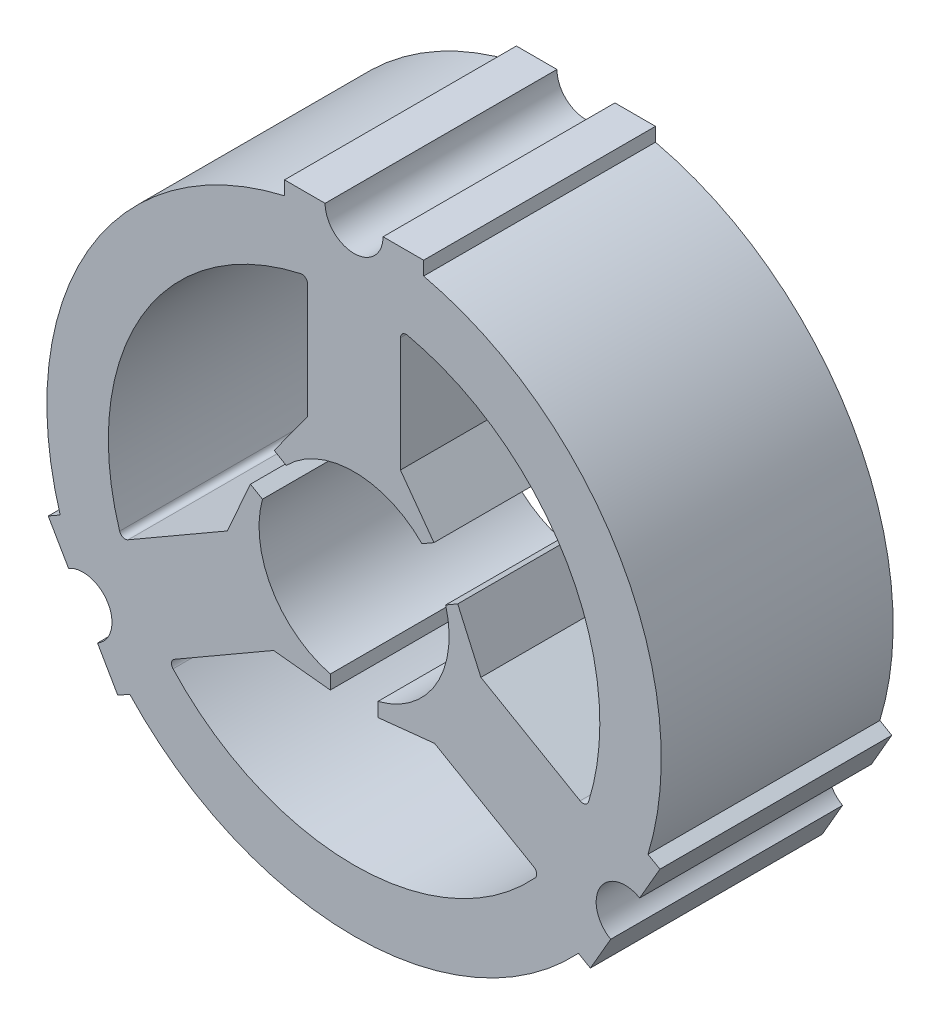
SolidWorks part; units mm, degrees
ref_plane "前视基准面" through (0, 0, 0) normal (0, 0, 1) x (1, 0, 0)
ref_plane "上视基准面" through (0, 0, 0) normal (0, 1, 0) x (1, 0, 0)
ref_plane "右视基准面" through (0, 0, 0) normal (1, 0, 0) x (0, 0, -1)
sketch "草图1" plane through (0, 0, 0) normal (0, 0, 1) x (1, 0, 0)
  line L0 (-21.4536, 0) -> (25.5305, 0) construction
  line L1 (0, 19.7631) -> (0, -19.5145) construction
  line L2 (-3, 13.5) -> (-3, 12.9059)
  line L3 (-1.25, 13.5) -> (-3, 13.5)
  line L4 (1.25, 13.5) -> (3, 13.5)
  line L5 (3, 13.5) -> (3, 12.9059)
  line L6 (13.1913, -4.1519) -> (12.6768, -3.8549)
  line L7 (12.3163, -5.6675) -> (13.1913, -4.1519)
  line L8 (11.0663, -7.8325) -> (10.1913, -9.3481)
  line L9 (10.1913, -9.3481) -> (9.6768, -9.051)
  line L10 (-10.1913, -9.3481) -> (-9.6768, -9.051)
  line L11 (-11.0663, -7.8325) -> (-10.1913, -9.3481)
  line L12 (-12.3163, -5.6675) -> (-13.1913, -4.1519)
  line L13 (-13.1913, -4.1519) -> (-12.6768, -3.8549)
  arc A0 (-3, 12.9059) -> (-12.6768, -3.8549) centre (0, 0) ccw
  circle A1 centre (0, 0) radius 4.1
  arc A2 (-1.25, 13.5) -> (1.25, 13.5) centre (0, 13.5) ccw
  arc A3 (12.3163, -5.6675) -> (11.0663, -7.8325) centre (11.6913, -6.75) ccw
  arc A4 (-11.0663, -7.8325) -> (-12.3163, -5.6675) centre (-11.6913, -6.75) ccw
  arc A5 (12.6768, -3.8549) -> (3, 12.9059) centre (0, 0) ccw
  arc A6 (-9.6768, -9.051) -> (9.6768, -9.051) centre (0, 0) ccw
  circle A7 centre (0, 0) radius 13.5 construction
  point P31 (0, 0)
  dimension "D1" = 26.5
  dimension "D2" = 8.2
  dimension "D3" = 13.5
  dimension "D4" = 2.5
  dimension "D7" = 27
  dimension "D5" = 6
  dimension "D6" = 3
extrude "凸台-拉伸1" add sketch "草图1" along normal blind 10
sketch "草图2" plane through (0, 0, 0) normal (0, 0, 1) x (1, 0, 0)
  line L0 (-18.2914, 0) -> (18.1831, 0) construction
  line L1 (0, 18.2481) -> (0, -17.8941) construction
  line L2 (0, 0) -> (17.302, -9.9893) construction
  line L3 (-7.749, -6.7833) -> (-3.47, -4.3128)
  line L4 (-3.47, -4.3128) -> (-1.025, -4.5698)
  line L5 (0, 0) -> (-16.8155, -9.7084) construction
  line L6 (-1.025, -4.5698) -> (-1.025, -3.9698)
  line L7 (1.025, -4.5698) -> (1.025, -3.9698)
  line L8 (3.47, -4.3128) -> (1.025, -4.5698)
  line L9 (7.749, -6.7833) -> (3.47, -4.3128)
  arc A0 (-7.8082, -7.1689) -> (7.8082, -7.1689) centre (0, 0) ccw
  circle A1 centre (0, 0) radius 4.1 construction
  arc A2 (-1.025, -3.9698) -> (1.025, -3.9698) centre (0, 0) ccw
  arc A3 (7.8082, -7.1689) -> (7.749, -6.7833) centre (7.624, -6.9998) ccw
  arc A4 (-7.8082, -7.1689) -> (-7.749, -6.7833) centre (-7.624, -6.9998) cw
  point P19 (1.025, -4.2698)
  point P21 (8.015, -6.9369)
  point P24 (-8.015, -6.9369)
  dimension "D2" = 21.2
  dimension "D8" = 0.25
  dimension "D1" = 120
  dimension "D3" = 120
  dimension "D4" = 2
  dimension "D5" = 144
  dimension "D6" = 2.05
  dimension "D7" = 0.6
extrude "切除-拉伸1" cut sketch "草图2" along normal blind 10
pattern_circular "阵列(圆周)1" count 3 over 360 about axis through (0, 0, 0) along (0, 0, 1) of "切除-拉伸1"
